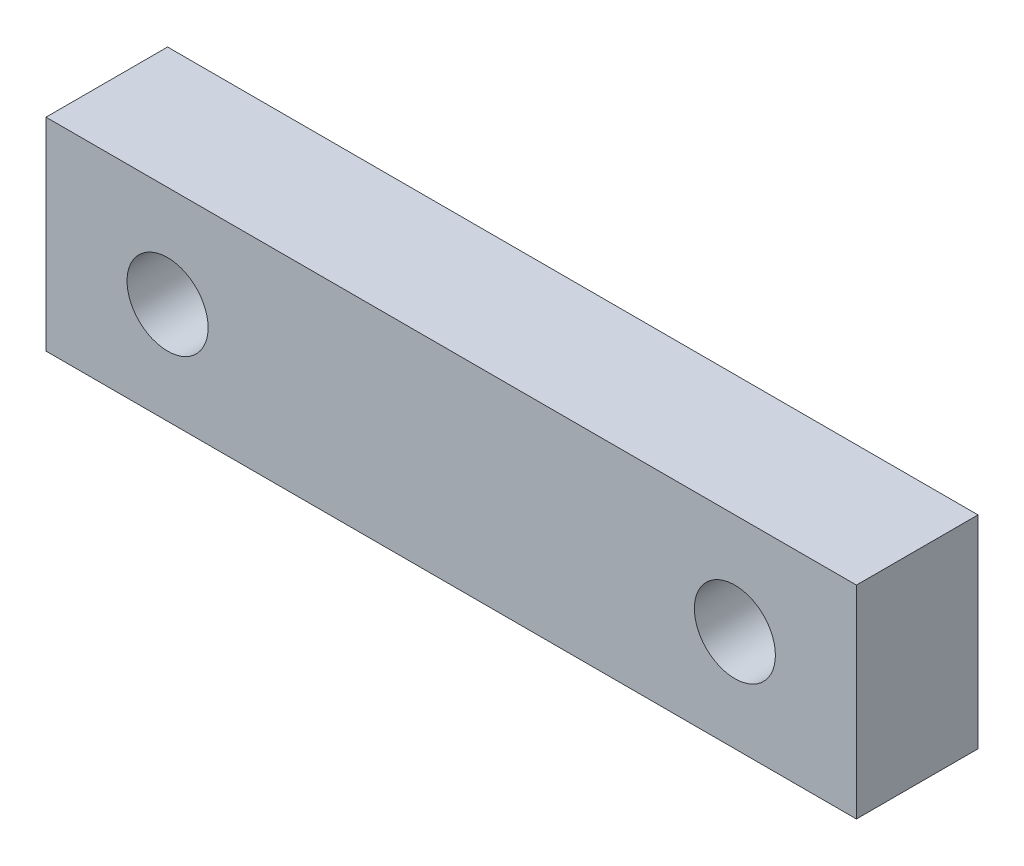
SolidWorks part; units mm, degrees
ref_plane "Front Plane" through (0, 0, 0) normal (0, 0, 1) x (1, 0, 0)
ref_plane "Top Plane" through (0, 0, 0) normal (0, 1, 0) x (1, 0, 0)
ref_plane "Right Plane" through (0, 0, 0) normal (1, 0, 0) x (0, 0, -1)
sketch "Sketch1" plane through (0, 0, 0) normal (0, 0, 1) x (1, 0, 0)
  line L0 (-94.6517, 19.0413) -> (-74.6517, 19.0413)
  line L1 (-74.6517, 19.0413) -> (-74.6517, 14.0413)
  line L2 (-74.6517, 14.0413) -> (-94.6517, 14.0413)
  line L3 (-94.6517, 14.0413) -> (-94.6517, 19.0413)
  circle A0 centre (-91.6517, 16.5413) radius 1
  circle A1 centre (-77.6517, 16.5413) radius 1
extrude "Boss-Extrude1" add sketch "Sketch1" along normal blind 3
